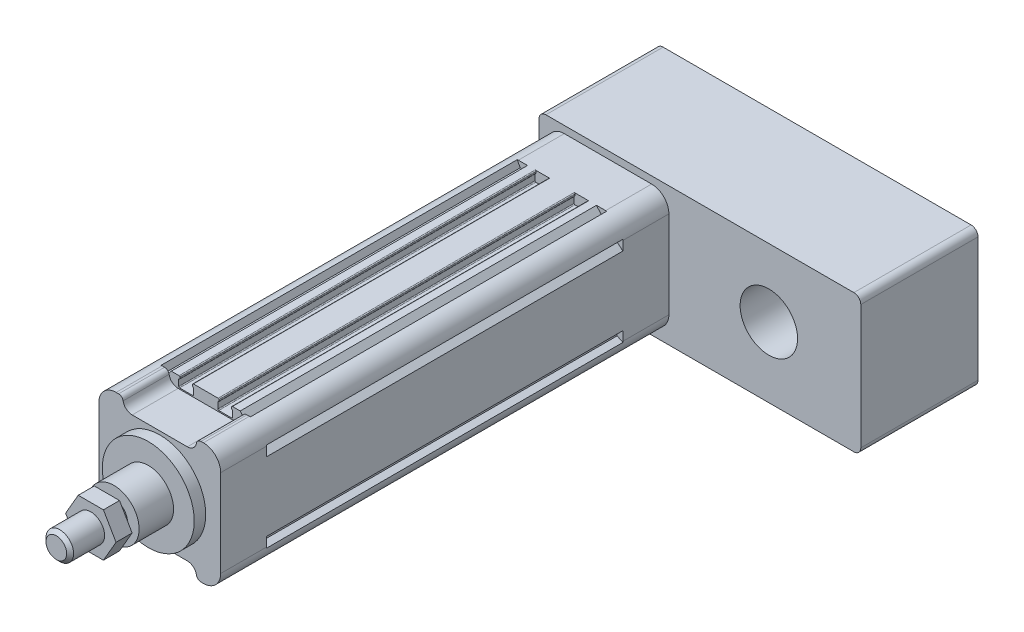
SolidWorks part; units mm, degrees
ref_plane "Front" through (0, 0, 0) normal (0, 0, 1) x (1, 0, 0)
ref_plane "Top" through (0, 0, 0) normal (0, 1, 0) x (1, 0, 0)
ref_plane "Right" through (0, 0, 0) normal (1, 0, 0) x (0, 0, -1)
sketch "草图1" plane through (0, 0, 0) normal (0, 0, 1) x (1, 0, 0)
  line L0 (19.7737, 3) -> (23.3, 3)
  line L1 (23.3, 3) -> (23.3, -3)
  line L2 (23.3, -3) -> (19.7737, -3)
  line L3 (-19.7737, -3) -> (-23.3, -3)
  line L4 (-23.3, -3) -> (-23.3, 3)
  line L5 (-23.3, 3) -> (-19.7737, 3)
  line L6 (-18.2, 24) -> (-19.4434, 26.4869)
  line L7 (-26.4869, 19.4434) -> (-24, 18.2)
  line L8 (-24, 18.2) -> (-24, 17.1)
  line L9 (-24, 17.1) -> (-26.5, 15)
  line L10 (-26.5, 15) -> (-26.5, -15)
  line L11 (-26.5, -15) -> (-24, -17.1)
  line L12 (-24, -17.1) -> (-24, -18.2)
  line L13 (-24, -18.2) -> (-26.4869, -19.4434)
  line L14 (-19.4434, -26.4869) -> (-18.2, -24)
  line L15 (-18.2, -24) -> (-17.1, -24)
  line L16 (-17.1, -24) -> (-15, -26.5)
  line L17 (-15, -26.5) -> (-11.65, -26.5)
  line L18 (-11.25, -26.1) -> (-11.25, -25.6)
  line L19 (-11.65, -25.2) -> (-11.75, -25.2)
  line L20 (-11.75, -25.2) -> (-11.75, -22.4)
  line L21 (-11.35, -22) -> (-5.65, -22)
  line L22 (-5.25, -22.4) -> (-5.25, -25.2)
  line L23 (-5.25, -25.2) -> (-5.35, -25.2)
  line L24 (-5.75, -25.6) -> (-5.75, -26.1)
  line L25 (-5.35, -26.5) -> (5.35, -26.5)
  line L26 (5.75, -26.1) -> (5.75, -25.6)
  line L27 (5.35, -25.2) -> (5.25, -25.2)
  line L28 (5.25, -25.2) -> (5.25, -22.4)
  line L29 (5.65, -22) -> (11.35, -22)
  line L30 (11.75, -22.4) -> (11.75, -25.2)
  line L31 (11.75, -25.2) -> (11.65, -25.2)
  line L32 (11.25, -25.6) -> (11.25, -26.1)
  line L33 (11.65, -26.5) -> (15, -26.5)
  line L34 (15, -26.5) -> (17.1, -24)
  line L35 (17.1, -24) -> (18.2, -24)
  line L36 (18.2, -24) -> (19.4434, -26.4869)
  line L37 (26.4869, -19.4434) -> (24, -18.2)
  line L38 (24, -18.2) -> (24, -17.1)
  line L39 (24, -17.1) -> (26.5, -15)
  line L40 (26.5, -15) -> (26.5, 15)
  line L41 (26.5, 15) -> (24, 17.1)
  line L42 (24, 17.1) -> (24, 18.2)
  line L43 (24, 18.2) -> (26.4869, 19.4434)
  line L44 (19.4434, 26.4869) -> (18.2, 24)
  line L45 (18.2, 24) -> (17.1, 24)
  line L46 (17.1, 24) -> (15, 26.5)
  line L47 (15, 26.5) -> (11.65, 26.5)
  line L48 (11.25, 26.1) -> (11.25, 25.6)
  line L49 (11.65, 25.2) -> (11.75, 25.2)
  line L50 (11.75, 25.2) -> (11.75, 22.4)
  line L51 (11.35, 22) -> (5.65, 22)
  line L52 (5.25, 22.4) -> (5.25, 25.2)
  line L53 (5.25, 25.2) -> (5.35, 25.2)
  line L54 (5.75, 25.6) -> (5.75, 26.1)
  line L55 (5.35, 26.5) -> (-5.35, 26.5)
  line L56 (-5.75, 26.1) -> (-5.75, 25.6)
  line L57 (-5.35, 25.2) -> (-5.25, 25.2)
  line L58 (-5.25, 25.2) -> (-5.25, 22.4)
  line L59 (-5.65, 22) -> (-11.35, 22)
  line L60 (-11.75, 22.4) -> (-11.75, 25.2)
  line L61 (-11.75, 25.2) -> (-11.65, 25.2)
  line L62 (-11.25, 25.6) -> (-11.25, 26.1)
  line L63 (-11.65, 26.5) -> (-15, 26.5)
  line L64 (-15, 26.5) -> (-17.1, 24)
  line L65 (-17.1, 24) -> (-18.2, 24)
  arc A0 (19.7737, 3) -> (-19.7737, 3) centre (0, 0) ccw
  arc A1 (-19.7737, -3) -> (19.7737, -3) centre (0, 0) ccw
  circle A2 centre (19, 19) radius 2.1
  circle A3 centre (19, -19) radius 2.1
  circle A4 centre (-19, -19) radius 2.1
  circle A5 centre (-19, 19) radius 2.1
  arc A6 (-19.4434, 26.4869) -> (-26.4869, 19.4434) centre (-19, 19) ccw
  arc A7 (-26.4869, -19.4434) -> (-19.4434, -26.4869) centre (-19, -19) ccw
  arc A8 (-11.65, -26.5) -> (-11.25, -26.1) centre (-11.65, -26.1) ccw
  arc A9 (-11.25, -25.6) -> (-11.65, -25.2) centre (-11.65, -25.6) ccw
  arc A10 (-11.35, -22) -> (-11.75, -22.4) centre (-11.35, -22.4) ccw
  arc A11 (-5.25, -22.4) -> (-5.65, -22) centre (-5.65, -22.4) ccw
  arc A12 (-5.35, -25.2) -> (-5.75, -25.6) centre (-5.35, -25.6) ccw
  arc A13 (-5.75, -26.1) -> (-5.35, -26.5) centre (-5.35, -26.1) ccw
  arc A14 (5.35, -26.5) -> (5.75, -26.1) centre (5.35, -26.1) ccw
  arc A15 (5.75, -25.6) -> (5.35, -25.2) centre (5.35, -25.6) ccw
  arc A16 (5.65, -22) -> (5.25, -22.4) centre (5.65, -22.4) ccw
  arc A17 (11.75, -22.4) -> (11.35, -22) centre (11.35, -22.4) ccw
  arc A18 (11.65, -25.2) -> (11.25, -25.6) centre (11.65, -25.6) ccw
  arc A19 (11.25, -26.1) -> (11.65, -26.5) centre (11.65, -26.1) ccw
  arc A20 (19.4434, -26.4869) -> (26.4869, -19.4434) centre (19, -19) ccw
  arc A21 (26.4869, 19.4434) -> (19.4434, 26.4869) centre (19, 19) ccw
  arc A22 (11.65, 26.5) -> (11.25, 26.1) centre (11.65, 26.1) ccw
  arc A23 (11.25, 25.6) -> (11.65, 25.2) centre (11.65, 25.6) ccw
  arc A24 (11.35, 22) -> (11.75, 22.4) centre (11.35, 22.4) ccw
  arc A25 (5.25, 22.4) -> (5.65, 22) centre (5.65, 22.4) ccw
  arc A26 (5.35, 25.2) -> (5.75, 25.6) centre (5.35, 25.6) ccw
  arc A27 (5.75, 26.1) -> (5.35, 26.5) centre (5.35, 26.1) ccw
  arc A28 (-5.35, 26.5) -> (-5.75, 26.1) centre (-5.35, 26.1) ccw
  arc A29 (-5.75, 25.6) -> (-5.35, 25.2) centre (-5.35, 25.6) ccw
  arc A30 (-5.65, 22) -> (-5.25, 22.4) centre (-5.65, 22.4) ccw
  arc A31 (-11.75, 22.4) -> (-11.35, 22) centre (-11.35, 22.4) ccw
  arc A32 (-11.65, 25.2) -> (-11.25, 25.6) centre (-11.65, 25.6) ccw
  arc A33 (-11.25, 26.1) -> (-11.65, 26.5) centre (-11.65, 26.1) ccw
extrude "凸台-拉伸1" add sketch "草图1" along normal blind 155
sketch "草图6" plane through (0, 0, 155) normal (0, 0, 1) x (1, 0, 0)
  line L0 (0, 0) -> (19, 0) construction
  line L2 (-26.5, -19) -> (-26.5, 19)
  line L3 (-19, 26.5) -> (-17.9161, 26.5)
  line L4 (26.5, -19) -> (26.5, 19)
  line L5 (-26.5, -26.5) -> (26.5, 26.5) construction
  line L6 (-26.5, 26.5) -> (26.5, -26.5) construction
  line L7 (-12, 21.5) -> (12, 21.5)
  line L9 (19, 26.5) -> (17.9161, 26.5)
  line L10 (19, -26.5) -> (17.9161, -26.5)
  line L11 (-12, -21.5) -> (12, -21.5)
  line L12 (-19, -26.5) -> (-17.9161, -26.5)
  arc A0 (12, 21.5) -> (15.9441, 24.8333) centre (12, 25.5) ccw
  arc A1 (-15.9441, 24.8333) -> (-12, 21.5) centre (-12, 25.5) ccw
  arc A2 (-15.9441, 24.8333) -> (-17.9161, 26.5) centre (-17.9161, 24.5) ccw
  arc A3 (15.9441, 24.8333) -> (17.9161, 26.5) centre (17.9161, 24.5) cw
  arc A4 (-26.5, -19) -> (-19, -26.5) centre (-19, -19) ccw
  arc A5 (19, -26.5) -> (26.5, -19) centre (19, -19) ccw
  arc A6 (26.5, 19) -> (19, 26.5) centre (19, 19) ccw
  arc A7 (-26.5, 19) -> (-19, 26.5) centre (-19, 19) cw
  arc A8 (15.9441, -24.8333) -> (17.9161, -26.5) centre (17.9161, -24.5) ccw
  arc A9 (12, -21.5) -> (15.9441, -24.8333) centre (12, -25.5) cw
  arc A10 (-15.9441, -24.8333) -> (-12, -21.5) centre (-12, -25.5) cw
  arc A11 (-15.9441, -24.8333) -> (-17.9161, -26.5) centre (-17.9161, -24.5) cw
  point P0 (0, 0)
  point P9 (0, 21.5)
  point P13 (20, 20.8461)
  point P16 (-12, 20.8461)
  dimension "D5" = 4
  dimension "D6" = 2
  dimension "D7" = 2
  dimension "D9" = 7.5
  dimension "D1" = 53
  dimension "D2" = 53
  dimension "D3" = 26.5
  dimension "D4" = 24
  dimension "D8" = 5
extrude "凸台-拉伸2" add sketch "草图6" along normal blind 20
sketch "草图7" plane through (0, 0, 175) normal (0, 0, 1) x (1, 0, 0)
  circle A0 centre (0, 0) radius 20
  dimension "D1" = 40
extrude "凸台-拉伸3" add sketch "草图7" along normal blind 5
sketch "草图9" plane through (0, 0, 180) normal (0, 0, 1) x (1, 0, 0)
  circle A0 centre (0, 0) radius 11
  dimension "D1" = 22
extrude "凸台-拉伸4" add sketch "草图9" along normal blind 15
sketch "草图10" plane through (0, 0, 195) normal (0, 0, 1) x (1, 0, 0)
  circle A0 centre (0, 0) radius 6
  dimension "D1" = 12
extrude "凸台-拉伸5" add sketch "草图10" along normal blind 25
sketch "草图11" plane through (0, 0, 0) normal (0, 0, -1) x (-1, 0, 0)
  line L1 (-19, -26.5) -> (19, -26.5)
  line L2 (-26.5, -19) -> (-26.5, 19)
  line L3 (-19, 26.5) -> (19, 26.5)
  line L4 (26.5, -19) -> (26.5, 19)
  line L5 (-26.5, -26.5) -> (26.5, 26.5) construction
  line L6 (-26.5, 26.5) -> (26.5, -26.5) construction
  arc A0 (-26.5, -19) -> (-19, -26.5) centre (-19, -19) ccw
  arc A1 (19, -26.5) -> (26.5, -19) centre (19, -19) ccw
  arc A2 (26.5, 19) -> (19, 26.5) centre (19, 19) ccw
  arc A3 (-26.5, 19) -> (-19, 26.5) centre (-19, 19) cw
  point P0 (0, 0)
  dimension "D3" = 7.5
  dimension "D1" = 53
  dimension "D2" = 53
extrude "凸台-拉伸6" add sketch "草图11" along normal blind 20
sketch "草图12" plane through (0, 0, -20) normal (0, 0, -1) x (-1, 0, 0)
  line L1 (-107, -30.4042) -> (27, -30.4042)
  line L2 (-110, -27.4042) -> (-110, 26.5958)
  line L3 (-107, 29.5958) -> (27, 29.5958)
  line L4 (30, -27.4042) -> (30, 26.5958)
  line L5 (-110, -30.4042) -> (30, 29.5958) construction
  line L6 (-110, 29.5958) -> (30, -30.4042) construction
  arc A0 (27, 29.5958) -> (30, 26.5958) centre (27, 26.5958) cw
  arc A1 (30, -27.4042) -> (27, -30.4042) centre (27, -27.4042) cw
  arc A2 (-110, -27.4042) -> (-107, -30.4042) centre (-107, -27.4042) ccw
  arc A3 (-110, 26.5958) -> (-107, 29.5958) centre (-107, 26.5958) cw
  point P0 (-40, -0.4042)
  dimension "D4" = 3
  dimension "D1" = 60
  dimension "D2" = 140
  dimension "D3" = 30
extrude "凸台-拉伸7" add sketch "草图12" along normal blind 51
sketch "草图13" plane through (0, 0, -20) normal (0, 0, 1) x (1, 0, 0)
  circle A0 centre (70, 0) radius 12.5
  dimension "D2" = 25
  dimension "D1" = 70
extrude "切除-拉伸2" cut sketch "草图13" against normal blind 30
hole_wizard "M6 螺纹孔1" positions "草图14" profile "草图15" tap size "M6" standard "GB"
sketch "草图14" plane through (0, 0, -71) normal (0, 0, -1) x (-1, 0, 0)
  line L0 (30, -27.4042) -> (30, 26.5958) construction
  point P0 (19, -19)
  dimension "D1" = 11
  dimension "D2" = 19
sketch "草图15" plane through (-19, -19, -71) normal (1, 0, 0) x (0, 1, 0)
  line L0 (0, 0) -> (0, 16.5022)
  line L1 (0, 16.5022) -> (2.5, 15)
  line L2 (2.5, 15) -> (2.5, 0)
  line L5 (2.5, 0) -> (0, 0)
  line L10 (0, 16.5022) -> (-2.5, 15) construction
  line L11 (0, -6.35) -> (0, 107.95) construction
  dimension "螺纹孔钻头直径" = 5
  dimension "螺纹孔钻头深度" = 15
  dimension "导头角度" = 118
cosmetic thread "孔螺蚊线4" parameters "D1"=12, "D2"=6
pattern_linear "阵列(线性)1" count 2 spacing 38 along (0, 1, 0) count 2 spacing 38 along (1, 0, 0) of "M6 螺纹孔1"
hole_wizard "M6 螺纹孔2" positions "草图16" profile "草图17" tap size "M6" standard "GB"
sketch "草图16" plane through (0, 0, -71) normal (0, 0, -1) x (-1, 0, 0)
  circle A1 centre (-19, 19) radius 2.5 construction
  circle A2 centre (-19, -19) radius 2.5 construction
  point P0 (-84, -19)
  point P2 (-84, 19)
  dimension "D3" = 65
  dimension "D1" = 19
  dimension "D2" = 19
  dimension "D4" = 65
sketch "草图17" plane through (84, -19, -71) normal (1, 0, 0) x (0, 1, 0)
  line L0 (0, 0) -> (0, 16.5022)
  line L1 (0, 16.5022) -> (2.5, 15)
  line L2 (2.5, 15) -> (2.5, 0)
  line L5 (2.5, 0) -> (0, 0)
  line L10 (0, 16.5022) -> (-2.5, 15) construction
  line L11 (0, -6.35) -> (0, 107.95) construction
  dimension "螺纹孔钻头直径" = 5
  dimension "螺纹孔钻头深度" = 15
  dimension "导头角度" = 118
cosmetic thread "孔螺蚊线5" parameters "D1"=12, "D2"=6
cosmetic thread "孔螺蚊线6" parameters "D1"=12, "D2"=6
hole_wizard "M6 螺纹孔3" positions "草图19" profile "草图20" tap size "M6" standard "GB"
sketch "草图19" plane through (-26.5, 0, 0) normal (-1, 0, 0) x (0, 0, 1)
  line L0 (175, 19) -> (175, -19) construction
  point P0 (165, 11)
  point P2 (165, -11)
  dimension "D1" = 10
  dimension "D2" = 10
  dimension "D3" = 22
  dimension "D4" = 11
sketch "草图20" plane through (-26.5, 11, 165) normal (0, 1, 0) x (0, 0, 1)
  line L0 (0, 0) -> (0, 16.5022)
  line L1 (0, 16.5022) -> (2.5, 15)
  line L2 (2.5, 15) -> (2.5, 0)
  line L5 (2.5, 0) -> (0, 0)
  line L10 (0, 16.5022) -> (-2.5, 15) construction
  line L11 (0, -6.35) -> (0, 107.95) construction
  dimension "螺纹孔钻头直径" = 5
  dimension "螺纹孔钻头深度" = 15
  dimension "导头角度" = 118
cosmetic thread "孔螺蚊线7" parameters "D1"=12, "D2"=6
cosmetic thread "孔螺蚊线8" parameters "D1"=12, "D2"=6
hole_wizard "M6 螺纹孔4" positions "草图21" profile "草图22" tap size "M6" standard "GB"
sketch "草图21" plane through (-26.5, 0, 0) normal (-1, 0, 0) x (0, 0, 1)
  line L0 (-20, -27.4042) -> (-20, 26.5958) construction
  line L1 (-20, -19) -> (-20, 19) construction
  point P0 (-10, 11)
  point P2 (-10, -11)
  dimension "D1" = 10
  dimension "D2" = 10
  dimension "D3" = 11
  dimension "D4" = 11
sketch "草图22" plane through (-26.5, 11, -10) normal (0, 1, 0) x (0, 0, 1)
  line L0 (0, 0) -> (0, 16.5022)
  line L1 (0, 16.5022) -> (2.5, 15)
  line L2 (2.5, 15) -> (2.5, 0)
  line L5 (2.5, 0) -> (0, 0)
  line L10 (0, 16.5022) -> (-2.5, 15) construction
  line L11 (0, -6.35) -> (0, 107.95) construction
  dimension "螺纹孔钻头直径" = 5
  dimension "螺纹孔钻头深度" = 15
  dimension "导头角度" = 118
cosmetic thread "孔螺蚊线9" parameters "D1"=12, "D2"=6
cosmetic thread "孔螺蚊线10" parameters "D1"=12, "D2"=6
chamfer "倒角1" distance 1.5 angle 45 1 edges at (6, 0, 220)
sketch "草图23" plane through (0, 0, 195) normal (0, 0, 1) x (1, 0, 0)
  line L1 (10.9697, 0) -> (5.4848, 9.5)
  line L2 (5.4848, 9.5) -> (-5.4848, 9.5)
  line L3 (-5.4848, 9.5) -> (-10.9697, 0)
  line L4 (-10.9697, 0) -> (-5.4848, -9.5)
  line L5 (-5.4848, -9.5) -> (5.4848, -9.5)
  line L6 (5.4848, -9.5) -> (10.9697, 0)
  circle A0 centre (0, 0) radius 9.5 construction
  dimension "D1" = 19
extrude "凸台-拉伸8" add sketch "草图23" along normal blind 7 from offset 3
